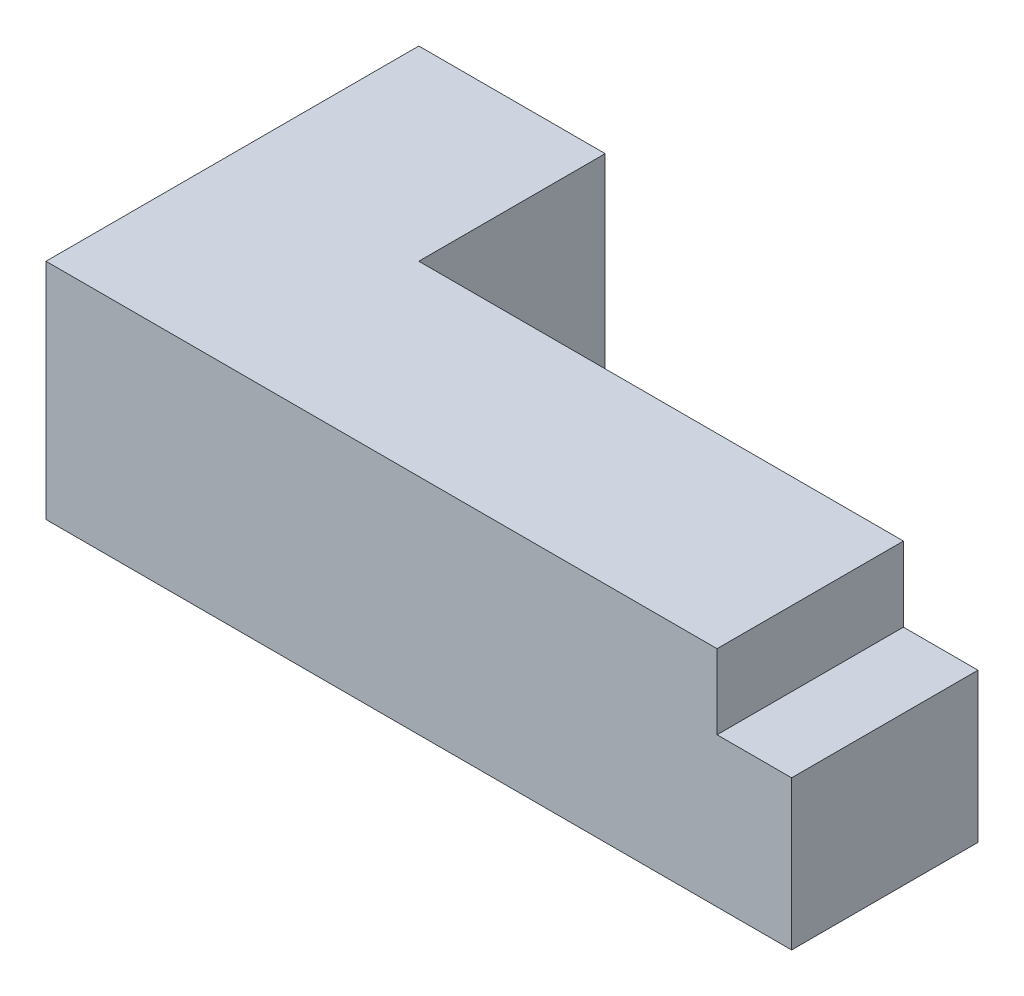
SolidWorks part; units mm, degrees
ref_plane "Přední rovina" through (0, 0, 0) normal (0, 0, 1) x (1, 0, 0)
ref_plane "Horní rovina" through (0, 0, 0) normal (0, 1, 0) x (1, 0, 0)
ref_plane "Pravá rovina" through (0, 0, 0) normal (1, 0, 0) x (0, 0, -1)
sketch "Skica1" plane through (0, 0, 0) normal (0, 1, 0) x (1, 0, 0)
  line L1 (0, 0) -> (100, 0)
  line L6 (0, 0) -> (0, 50)
  line L7 (0, 0) -> (100, 0)
  line L15 (0, 50) -> (25, 50)
  line L16 (25, 50) -> (25, 25)
  line L17 (25, 25) -> (100, 25)
  line L18 (100, 25) -> (100, 0)
  line L19 (0, 0) -> (0, 50)
  point P0 (100, 11.5549)
  dimension "D1" = 100
  dimension "D2" = 50
  dimension "D5" = 25
  dimension "D6" = 75
extrude "Přidat vysunutím1" add sketch "Skica1" along normal blind 30 contours L18 L17 L16 L15 L6 L1
sketch "Skica2" plane through (0, 0, 0) normal (0, 0, 1) x (1, 0, 0)
  line L1 (100, 30) -> (90, 30)
  line L2 (100, 30) -> (100, 20)
  line L3 (100, 20) -> (90, 20)
  line L4 (90, 30) -> (90, 20)
  dimension "D1" = 10
  dimension "D2" = 10
extrude "Odebrat vysunutím1" cut sketch "Skica2" against normal up to next
